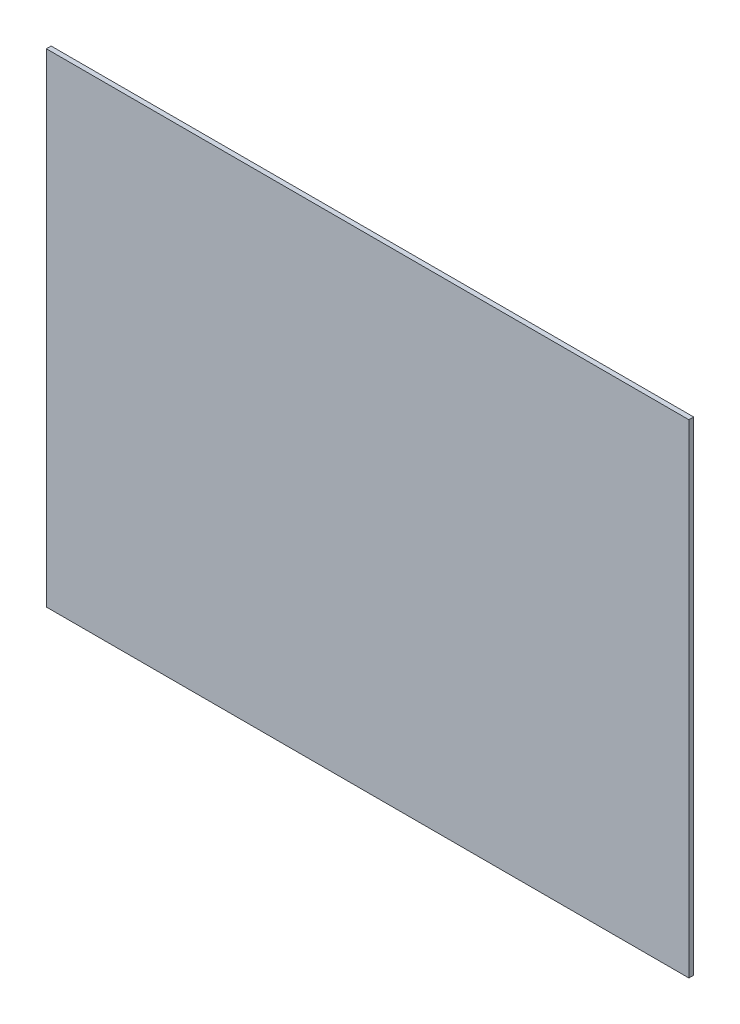
SolidWorks part; units mm, degrees
ref_plane "Front Plane" through (0, 0, 0) normal (0, 0, 1) x (1, 0, 0)
ref_plane "Top Plane" through (0, 0, 0) normal (0, 1, 0) x (1, 0, 0)
ref_plane "Right Plane" through (0, 0, 0) normal (1, 0, 0) x (0, 0, -1)
sketch "Sketch1" plane through (0, 0, 0) normal (0, 0, 1) x (1, 0, 0)
  line L1 (-202, 152) -> (202, 152)
  line L2 (-202, 152) -> (-202, -152)
  line L3 (-202, -152) -> (202, -152)
  line L4 (202, 152) -> (202, -152)
  line L5 (-202, 152) -> (202, -152) construction
  line L6 (-202, -152) -> (202, 152) construction
  point P0 (0, 0)
  dimension "D1" = 404
  dimension "D2" = 304
extrude "Boss-Extrude1" add sketch "Sketch1" along normal blind 3
